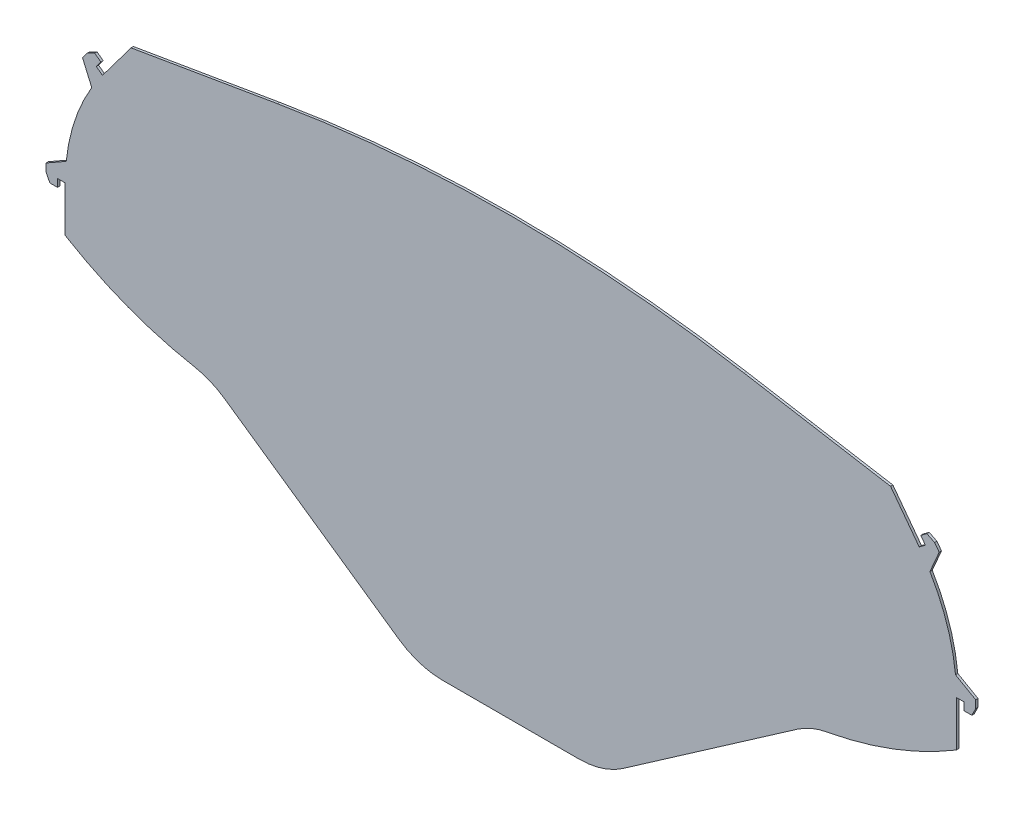
SolidWorks part; units mm, degrees
ref_plane "Front Plane" through (0, 0, 0) normal (0, 0, 1) x (1, 0, 0)
ref_plane "Top Plane" through (0, 0, 0) normal (0, 1, 0) x (1, 0, 0)
ref_plane "Right Plane" through (0, 0, 0) normal (1, 0, 0) x (0, 0, -1)
sketch "Sketch1" plane through (0, 0, 0) normal (0, 0, 1) x (1, 0, 0)
  line L0 (-24, -91.7648) -> (24, -91.7648)
  line L1 (0, 0) -> (0, -91.7648) construction
  line L2 (-10, 0) -> (-17, 10.2352)
  line L5 (-100.1804, -19.9556) -> (-60.7439, -13.2648)
  line L7 (-24, -91.7648) -> (-78.2662, -84.0567)
  line L8 (-17, 10.2352) -> (-26.9419, 9.1584)
  line L13 (-122.5, -58.7648) -> (122.5, -58.7648) construction
  line L14 (-60.7439, -13.2648) -> (-60.7439, -58.7648) construction
  line L15 (-113.5977, -28.7648) -> (-113.5977, -58.7648) construction
  line L16 (-10, 0) -> (10, 0)
  line L17 (10, 0) -> (17, 10.2352)
  line L18 (113.5977, -28.7648) -> (113.5977, -58.7648) construction
  line L19 (60.7439, -13.2648) -> (60.7439, -58.7648) construction
  line L20 (17, 10.2352) -> (26.9419, 9.1584)
  line L21 (24, -91.7648) -> (78.2662, -84.0567)
  line L22 (100.1804, -19.9556) -> (60.7439, -13.2648)
  line L23 (-17, 10.2352) -> (17, 10.2352) construction
  line L24 (0, 10.2352) -> (0, 0) construction
  arc A0 (-26.9419, 9.1584) -> (-43.4614, -1.4344) centre (-24.5729, -12.7137) ccw
  arc A1 (-43.4614, -1.4344) -> (-60.7439, -13.2648) centre (-64.9257, 11.383) cw
  arc A2 (-113.5977, -28.7648) -> (-100.1804, -19.9556) centre (-96.8349, -39.6739) cw
  arc A3 (-122.5, -58.7648) -> (-113.5977, -28.7648) centre (-67.5, -58.7648) cw
  arc A8 (-122.5, -58.7648) -> (-115.7111, -70.7648) centre (-108.5, -58.7648) ccw
  arc A9 (-115.7111, -70.7648) -> (-78.2662, -84.0567) centre (-64.2032, 14.9495) ccw
  arc A10 (115.7111, -70.7648) -> (78.2662, -84.0567) centre (64.2032, 14.9495) cw
  arc A11 (122.5, -58.7648) -> (115.7111, -70.7648) centre (108.5, -58.7648) cw
  arc A12 (122.5, -58.7648) -> (113.5977, -28.7648) centre (67.5, -58.7648) ccw
  arc A13 (113.5977, -28.7648) -> (100.1804, -19.9556) centre (96.8349, -39.6739) ccw
  arc A14 (43.4614, -1.4344) -> (60.7439, -13.2648) centre (64.9257, 11.383) ccw
  arc A15 (26.9419, 9.1584) -> (43.4614, -1.4344) centre (24.5729, -12.7137) cw
  dimension "D5" = 55
  dimension "D7" = 20
  dimension "D9" = 25
  dimension "D11" = 22
  dimension "D12" = 14
  dimension "D19" = 100
  dimension "D2" = 50.7439
  dimension "D3" = 102
  dimension "D4" = 10
  dimension "D6" = 14
  dimension "D8" = 40
  dimension "D10" = 58.7648
  dimension "D13" = 188.084
  dimension "D14" = 12.4
  dimension "D15" = 45.5
  dimension "D16" = 30
  dimension "D17" = 33
  dimension "D18" = 118.187
  dimension "D20" = 20
extrude "Main Shape" add sketch "Sketch1" along normal blind 0.6
sketch "Sketch2" plane through (0, 0, 0.6) normal (0, 0, 1) x (1, 0, 0)
  line L0 (0, 0) -> (0, -91.7648) construction
  line L1 (-24, -91.7648) -> (24, -91.7648) construction
  line L5 (-121, -58.7648) -> (-121, -56.7648)
  line L15 (-116, -58.7648) -> (-116, -70.5864)
  line L23 (113.5111, -43.4277) -> (119.6776, -41.3722) construction
  line L24 (113.5111, -43.4277) -> (106.4062, -22.1128) construction
  line L25 (110.3, -26.6648) -> (111.5, -28.2648)
  line L41 (-106.3, -29.6648) -> (-98.8487, -19.7297)
  line L42 (-60.7439, -13.2648) -> (-100.1804, -19.9556) construction
  line L43 (-98.8487, -19.7297) -> (-100.1804, -19.9556)
  line L44 (-116, -58.7648) -> (-118, -58.7648)
  line L45 (-118, -58.7648) -> (-118, -60.7648)
  line L46 (-118, -60.7648) -> (-120, -60.7648)
  line L47 (-120, -60.7648) -> (-121, -58.7648)
  line L48 (-121, -56.7648) -> (-115.7423, -53.7714)
  line L49 (-113.5111, -43.4277) -> (-106.4062, -22.1128) construction
  line L50 (-113.5111, -43.4277) -> (-119.6776, -41.3722) construction
  line L51 (-111.5, -28.2648) -> (-109.0898, -33.8141)
  line L52 (-108.3, -25.6648) -> (-110.3, -26.6648)
  line L53 (-106.7, -26.8648) -> (-108.3, -25.6648)
  line L54 (-107.9, -28.4648) -> (-106.7, -26.8648)
  line L55 (-106.3, -29.6648) -> (-107.9, -28.4648)
  line L56 (-110.3, -26.6648) -> (-111.5, -28.2648)
  line L57 (106.3, -29.6648) -> (107.9, -28.4648)
  line L58 (107.9, -28.4648) -> (106.7, -26.8648)
  line L59 (106.7, -26.8648) -> (108.3, -25.6648)
  line L60 (108.3, -25.6648) -> (110.3, -26.6648)
  line L61 (111.5, -28.2648) -> (109.0898, -33.8141)
  line L62 (121, -56.7648) -> (115.7423, -53.7714)
  line L63 (120, -60.7648) -> (121, -58.7648)
  line L64 (118, -60.7648) -> (120, -60.7648)
  line L65 (118, -58.7648) -> (118, -60.7648)
  line L66 (116, -58.7648) -> (118, -58.7648)
  line L67 (98.8487, -19.7297) -> (100.1804, -19.9556)
  line L68 (106.3, -29.6648) -> (98.8487, -19.7297)
  line L69 (116, -58.7648) -> (116, -70.5864)
  line L70 (121, -58.7648) -> (121, -56.7648)
  arc A9 (-106.3, -29.6648) -> (-116, -58.7648) centre (-67.5, -58.7648) ccw construction
  arc A11 (-113.5977, -28.7648) -> (-122.5, -58.7648) centre (-67.5, -58.7648) ccw construction
  arc A12 (-115.7423, -53.7714) -> (-109.0898, -33.8141) centre (-67.5, -58.7648) cw
  arc A13 (-107.5, -28.7648) -> (-117.5, -58.7648) centre (-67.5, -58.7648) ccw construction
  arc A14 (-105.1, -30.5648) -> (-114.5, -58.7648) centre (-67.5, -58.7648) ccw construction
  arc A15 (-105.1, -30.5648) -> (-107.5, -28.7648) centre (-106.3, -29.6648) ccw construction
  arc A16 (-117.5, -58.7648) -> (-114.5, -58.7648) centre (-116, -58.7648) ccw construction
  arc A18 (106.3, -29.6648) -> (116, -58.7648) centre (67.5, -58.7648) cw construction
  arc A19 (107.5, -28.7648) -> (117.5, -58.7648) centre (67.5, -58.7648) cw construction
  arc A21 (105.1, -30.5648) -> (114.5, -58.7648) centre (67.5, -58.7648) cw construction
  arc A22 (105.1, -30.5648) -> (107.5, -28.7648) centre (106.3, -29.6648) cw construction
  arc A23 (117.5, -58.7648) -> (114.5, -58.7648) centre (116, -58.7648) cw construction
  arc A24 (122.5, -58.7648) -> (116, -70.5864) centre (108.5, -58.7648) cw
  arc A25 (113.5977, -28.7648) -> (122.5, -58.7648) centre (67.5, -58.7648) cw
  arc A26 (100.1804, -19.9556) -> (113.5977, -28.7648) centre (96.8349, -39.6739) cw
  arc A33 (-122.5, -58.7648) -> (-115.7111, -70.7648) centre (-108.5, -58.7648) ccw construction
  arc A34 (-100.1804, -19.9556) -> (-113.5977, -28.7648) centre (-96.8349, -39.6739) ccw construction
  arc A35 (-100.1804, -19.9556) -> (-113.5977, -28.7648) centre (-96.8349, -39.6739) ccw
  arc A36 (-113.5977, -28.7648) -> (-122.5, -58.7648) centre (-67.5, -58.7648) ccw
  arc A37 (-122.5, -58.7648) -> (-116, -70.5864) centre (-108.5, -58.7648) ccw
  arc A38 (115.7423, -53.7714) -> (109.0898, -33.8141) centre (67.5, -58.7648) ccw
  point P24 (-113.5111, -43.4277)
  point P46 (113.5111, -43.4277)
  dimension "D1" = 1.5
  dimension "D2" = 5
  dimension "D3" = 2
  dimension "D7" = 5
  dimension "D4" = 2
  dimension "D5" = 2
  dimension "D6" = 2
  dimension "D8" = 5
extrude "Tabs" cut sketch "Sketch2" against normal through all both and the other way through all
sketch "Sketch5" plane through (0, 0, 0.6) normal (0, 0, 1) x (1, 0, 0)
  line L0 (-78.2662, -84.0567) -> (-24, -121.7648)
  line L1 (-24, -121.7648) -> (24, -121.7648)
  line L2 (24, -121.7648) -> (78.2662, -84.0567)
  line L3 (-78.2662, -84.0567) -> (-24, -91.7648) construction
  line L4 (24, -91.7648) -> (78.2662, -84.0567) construction
  line L5 (-24, -91.7648) -> (24, -91.7648) construction
  line L6 (24, -91.7648) -> (78.2662, -84.0567)
  line L7 (-24, -91.7648) -> (24, -91.7648)
  line L8 (-78.2662, -84.0567) -> (-24, -91.7648)
  dimension "D1" = 30
extrude "Chin guard" add sketch "Sketch5" against normal up to surface (0.6 mm away) up to face at (0, -39.2266, 0)
fillet "Fillet1" radius 20 4 edges at (-78.2662, -84.0567, 0.3) (78.2662, -84.0567, 0.3) (24, -121.7648, 0.3) (-24, -121.7648, 0.3)
sketch "Sketch6" plane through (0, 0, 0.6) normal (0, 0, 1) x (1, 0, 0)
  line L0 (-60.7439, -13.2648) -> (-98.8487, -19.7297) construction
  line L1 (98.8487, -19.7297) -> (60.7439, -13.2648) construction
  line L2 (-60.7439, -13.2648) -> (-60.7439, 16.7352)
  line L3 (-60.7439, 16.7352) -> (60.7439, 16.7352)
  line L4 (60.7439, 16.7352) -> (60.7439, -13.2648)
  arc A0 (-60.7439, -13.2648) -> (60.7439, -13.2648) centre (0, -371.2932) cw
  dimension "D1" = 30
extrude "Cut-Extrude1" cut sketch "Sketch6" against normal through all both and the other way through all
